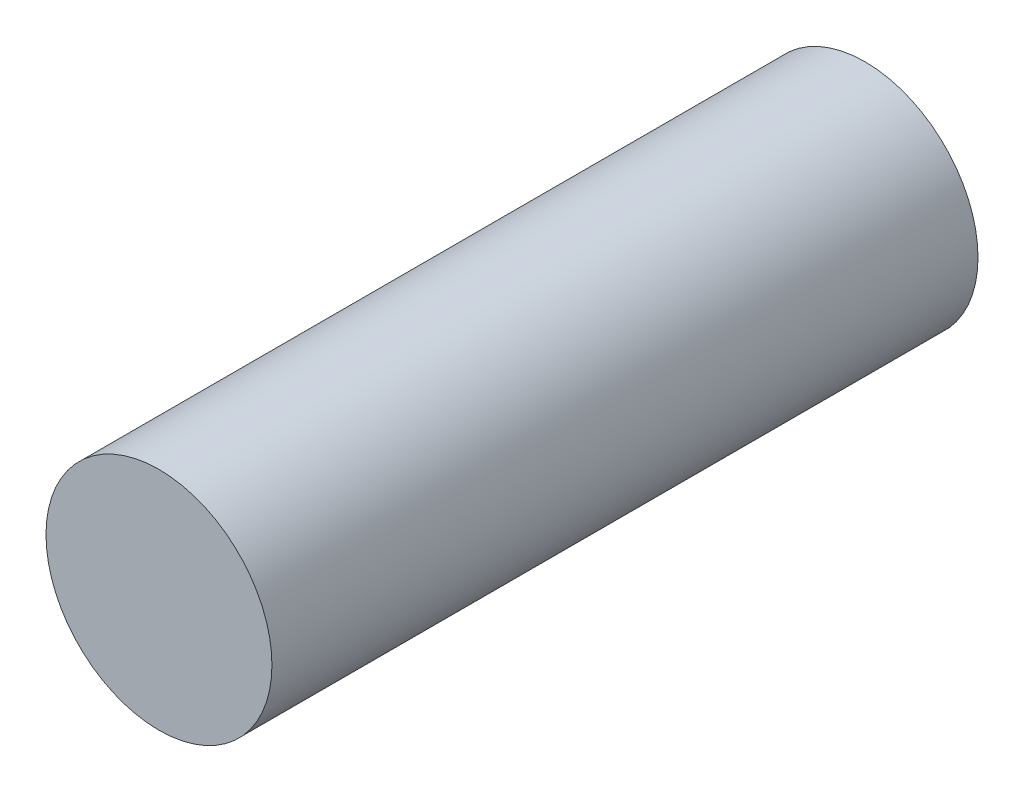
SolidWorks part; units mm, degrees
ref_plane "Plano frontal" through (0, 0, 0) normal (0, 0, 1) x (1, 0, 0)
ref_plane "Plano superior" through (0, 0, 0) normal (0, 1, 0) x (1, 0, 0)
ref_plane "Plano direito" through (0, 0, 0) normal (1, 0, 0) x (0, 0, -1)
sketch "Esboço1" plane through (0, 0, 0) normal (0, 0, 1) x (1, 0, 0)
  circle A0 centre (0, 0) radius 4
  dimension "D1" = 8
extrude "Ressalto-extrusão1" add sketch "Esboço1" along normal mid plane 25
